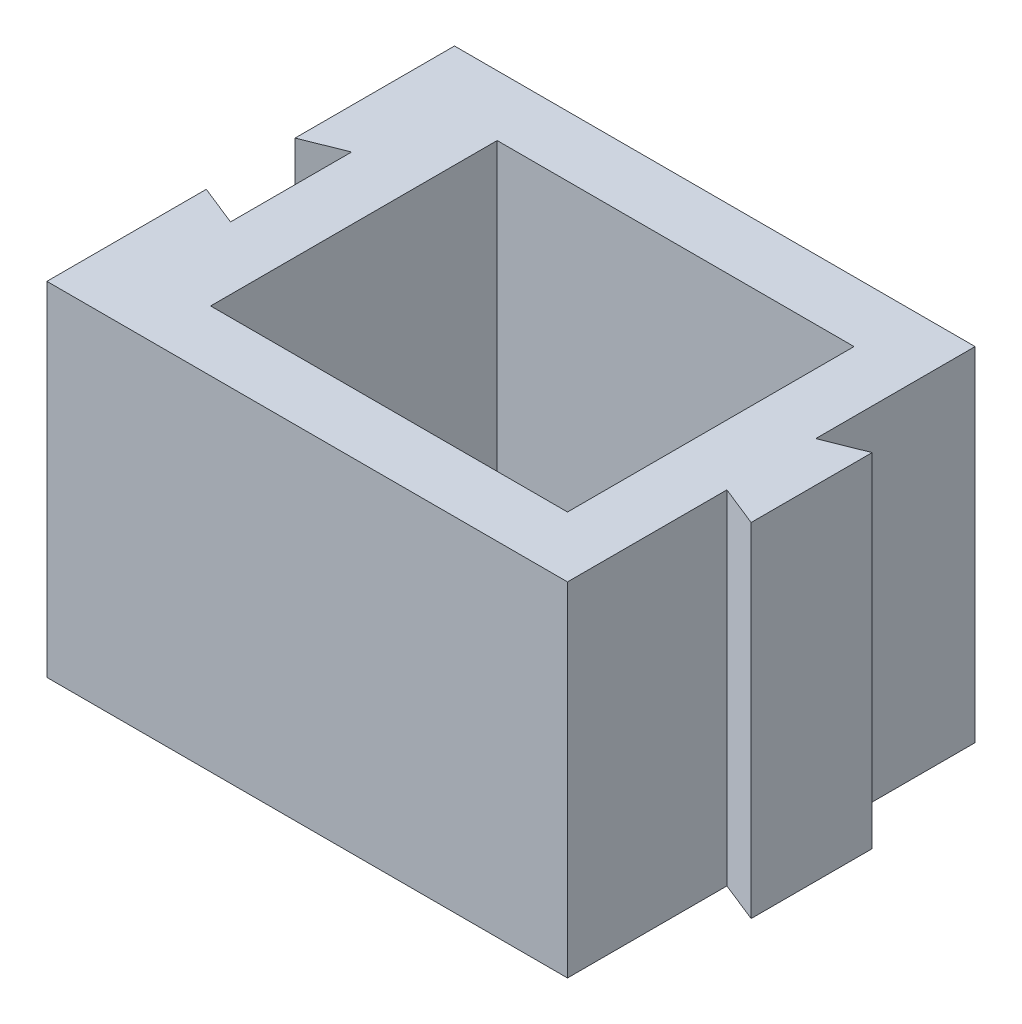
SolidWorks part; units mm, degrees
ref_plane "Front Plane" through (0, 0, 0) normal (0, 0, 1) x (1, 0, 0)
ref_plane "Top Plane" through (0, 0, 0) normal (0, 1, 0) x (1, 0, 0)
ref_plane "Right Plane" through (0, 0, 0) normal (1, 0, 0) x (0, 0, -1)
sketch "Sketch1" plane through (0, 0, 0) normal (0, 1, 0) x (1, 0, 0)
  line L0 (-32.25, 5.5) -> (-27.25, 7.5)
  line L1 (-32.25, 25.25) -> (32.25, 25.25)
  line L2 (-32.25, 25.25) -> (-32.25, -25.25)
  line L3 (-32.25, -25.25) -> (32.25, -25.25)
  line L4 (32.25, 25.25) -> (32.25, -25.25)
  line L5 (-32.25, 25.25) -> (32.25, -25.25) construction
  line L6 (-32.25, -25.25) -> (32.25, 25.25) construction
  line L7 (-27.25, 7.5) -> (-27.25, -7.5)
  line L8 (-27.25, -7.5) -> (-32.25, -5.5)
  line L9 (-32.25, -5.5) -> (-32.25, 5.5)
  line L10 (32.25, 5.5) -> (37.25, 7.5)
  line L11 (37.25, 7.5) -> (37.25, -7.5)
  line L12 (37.25, -7.5) -> (32.25, -5.5)
  line L13 (32.25, 5.5) -> (32.25, -5.5)
  line L14 (-32.25, 25.25) -> (-27.25, 7.5) construction
  line L15 (-27.25, -7.5) -> (-32.25, -25.25) construction
  line L16 (32.25, 25.25) -> (37.25, 7.5) construction
  point P0 (0, 0)
  dimension "D1" = 64.5
  dimension "D2" = 50.5
  dimension "D3" = 5
  dimension "D4" = 2
  dimension "D5" = 15
extrude "Boss-Extrude1" add sketch "Sketch1" along normal blind 42.5 contours L7 L8 L2 L3 L4 L1 L0 | L12 L11 L10 L4
sketch "Sketch2" plane through (0, 42.5, 0) normal (0, 1, 0) x (1, 0, 0)
  line L0 (-19.4647, -17.75) -> (-19.4647, 17.75)
  line L1 (-19.4647, 17.75) -> (24.75, 17.75)
  line L2 (24.75, 17.75) -> (24.75, -17.75)
  line L3 (24.75, -17.75) -> (-19.4647, -17.75)
  line L4 (-27.25, 7.5) -> (-27.25, -7.5) construction
  line L5 (-32.25, 25.25) -> (32.25, 25.25) construction
  line L6 (-32.25, -25.25) -> (32.25, -25.25) construction
  line L7 (32.25, 25.25) -> (32.25, 5.5) construction
  dimension "D1" = 7.7853
  dimension "D2" = 7.5
  dimension "D3" = 7.5
  dimension "D4" = 7.5
extrude "Cut-Extrude1" cut sketch "Sketch2" against normal up to surface (42.5 mm away) up to face at (1.6667, 0, 0)
